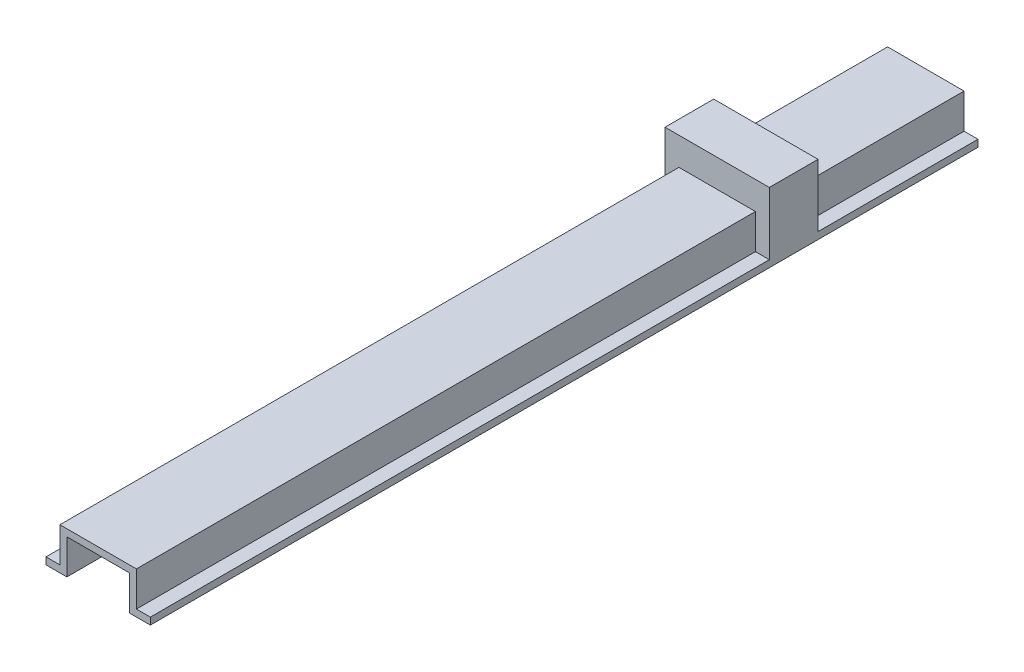
SolidWorks part; units mm, degrees
ref_plane "Front Plane" through (0, 0, 0) normal (0, 0, 1) x (1, 0, 0)
ref_plane "Top Plane" through (0, 0, 0) normal (0, 1, 0) x (1, 0, 0)
ref_plane "Right Plane" through (0, 0, 0) normal (1, 0, 0) x (0, 0, -1)
sketch "Sketch1" plane through (0, 0, 0) normal (0, 0, 1) x (1, 0, 0)
  line L0 (-5.366, -2.186) -> (-7.366, -2.186)
  line L1 (-4.366, 1.814) -> (4.634, 1.814)
  line L2 (-4.366, 1.814) -> (-4.366, -2.186)
  line L3 (7.634, -2.186) -> (5.634, -2.186)
  line L4 (4.634, 1.814) -> (4.634, -2.186)
  line L7 (-5.366, 2.814) -> (5.634, 2.814)
  line L8 (-5.366, 2.814) -> (-5.366, -2.186)
  line L9 (-4.366, -2.186) -> (-4.366, -3.186)
  line L10 (5.634, 2.814) -> (5.634, -2.186)
  line L11 (-4.366, -3.186) -> (-7.366, -3.186)
  line L12 (-7.366, -2.186) -> (-7.366, -3.186)
  line L14 (4.634, -2.186) -> (4.634, -3.186)
  line L15 (4.634, -3.186) -> (7.634, -3.186)
  line L16 (7.634, -2.186) -> (7.634, -3.186)
  point P0 (0, 0)
  point P6 (0.134, -0.0632)
  dimension "D1" = 9
  dimension "D2" = 4
  dimension "D3" = 11
  dimension "D4" = 5
  dimension "D5" = 1
  dimension "D6" = 1
  dimension "D7" = 3
  dimension "D8" = 3
  dimension "D9" = 1
  dimension "D10" = 1
  dimension "D11" = 1
  dimension "D12" = 1
  dimension "D13" = 5
  dimension "D14" = 4
extrude "Boss-Extrude1" add sketch "Sketch1" along normal blind 119
sketch "Sketch2" plane through (0, -2.186, 0) normal (0, 1, 0) x (1, 0, 0)
  line L0 (7.634, -119) -> (7.634, 0) construction
  line L1 (-7.366, -23) -> (7.634, -23)
  line L2 (-7.366, -23) -> (-7.366, -30)
  line L3 (-7.366, -30) -> (7.634, -30)
  line L4 (7.634, -23) -> (7.634, -30)
  line L5 (-7.366, -23) -> (7.634, -30) construction
  line L6 (-7.366, -30) -> (7.634, -23) construction
  line L8 (5.634, 0) -> (-5.366, 0) construction
  point P0 (0.134, -26.5)
  dimension "D1" = 15
  dimension "D2" = 23
  dimension "D3" = 7
extrude "Boss-Extrude2" add sketch "Sketch2" along normal blind 9
sketch "Sketch3" plane through (0, -2.186, 0) normal (0, -1, 0) x (1, 0, 0)
  line L1 (-4.366, 23) -> (4.634, 23)
  line L2 (-4.366, 23) -> (-4.366, 30)
  line L3 (-4.366, 30) -> (4.634, 30)
  line L4 (4.634, 23) -> (4.634, 30)
extrude "Cut-Extrude1" cut sketch "Sketch3" against normal blind 4
sketch "Sketch4" plane through (-7.366, 0, 0) normal (-1, 0, 0) x (0, 0, 1)
  line L0 (30, 6.814) -> (30, -2.186) construction
  line L1 (24, 5.814) -> (29, 5.814)
  line L2 (24, 5.814) -> (24, -1.186)
  line L3 (24, -1.186) -> (29, -1.186)
  line L4 (29, 5.814) -> (29, -1.186)
  line L5 (23, 6.814) -> (23, -2.186) construction
  line L6 (23, 6.814) -> (30, 6.814) construction
  dimension "D1" = 1
  dimension "D2" = 1
  dimension "D3" = 1
  dimension "D4" = 7
extrude "Cut-Extrude2" cut sketch "Sketch4" against normal blind 12
